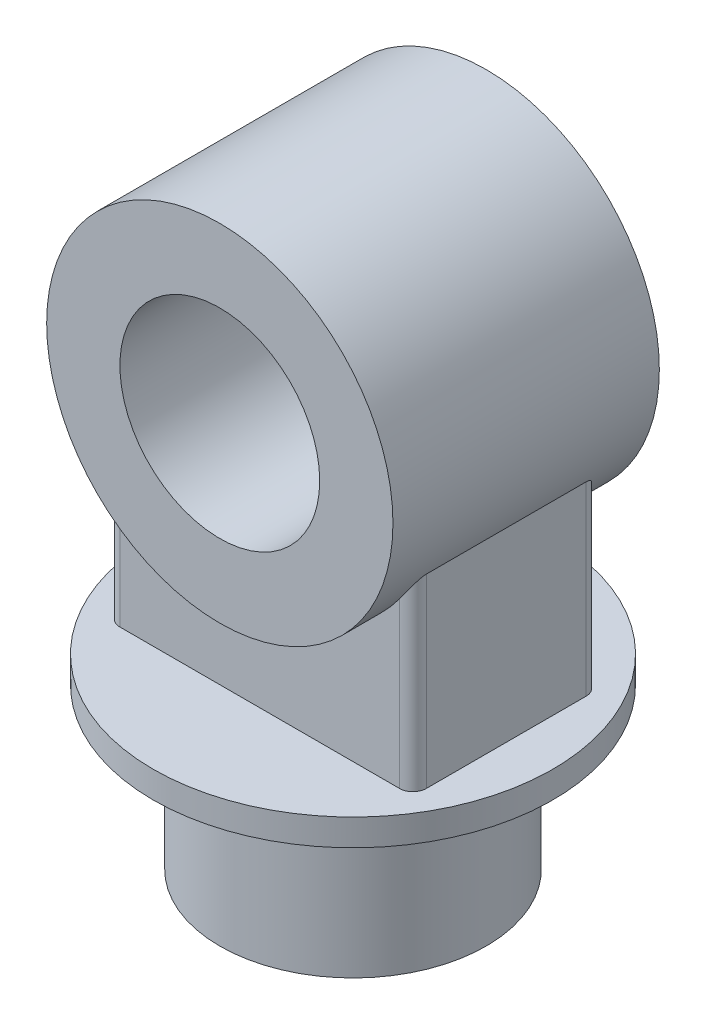
SolidWorks part; units mm, degrees
ref_plane "Front Plane" through (0, 0, 0) normal (0, 0, 1) x (1, 0, 0)
ref_plane "Top Plane" through (0, 0, 0) normal (0, 1, 0) x (1, 0, 0)
ref_plane "Right Plane" through (0, 0, 0) normal (1, 0, 0) x (0, 0, -1)
sketch "Sketch1" plane through (0, 0, 0) normal (0, 1, 0) x (1, 0, 0)
  circle A0 centre (0, 0) radius 100
  dimension "D1" = 200
extrude "Boss-Extrude1" add sketch "Sketch1" along normal blind 120
sketch "Sketch2" plane through (0, 120, 0) normal (0, 1, 0) x (1, 0, 0)
  circle A0 centre (0, 0) radius 150
  dimension "D1" = 300
extrude "Boss-Extrude2" add sketch "Sketch2" along normal blind 20
sketch "Sketch4" plane through (0, 0, 0) normal (0, 0, 1) x (1, 0, 0)
  line L0 (150, 140) -> (-150, 140) construction
  circle A0 centre (0, 340) radius 75
  circle A1 centre (0, 340) radius 130
  dimension "D1" = 150
  dimension "D2" = 260
  dimension "D3" = 200
extrude "Boss-Extrude3" add sketch "Sketch4" along normal mid plane 200 separate body
sketch "Sketch5" plane through (0, 140, 0) normal (0, 1, 0) x (1, 0, 0)
  line L1 (-115, -70) -> (115, -70)
  line L2 (-115, -70) -> (-115, 70)
  line L3 (-115, 70) -> (115, 70)
  line L4 (115, -70) -> (115, 70)
  line L5 (-115, -70) -> (115, 70) construction
  line L6 (-115, 70) -> (115, -70) construction
  point P0 (0, 0)
  dimension "D1" = 140
  dimension "D2" = 230
extrude "Boss-Extrude4" add sketch "Sketch5" along normal up to next
fillet "Fillet1" radius 10 4 edges at (-115, 209.6891, -70) (-115, 209.6891, 70) (115, 209.6891, -70) (115, 209.6891, 70)
